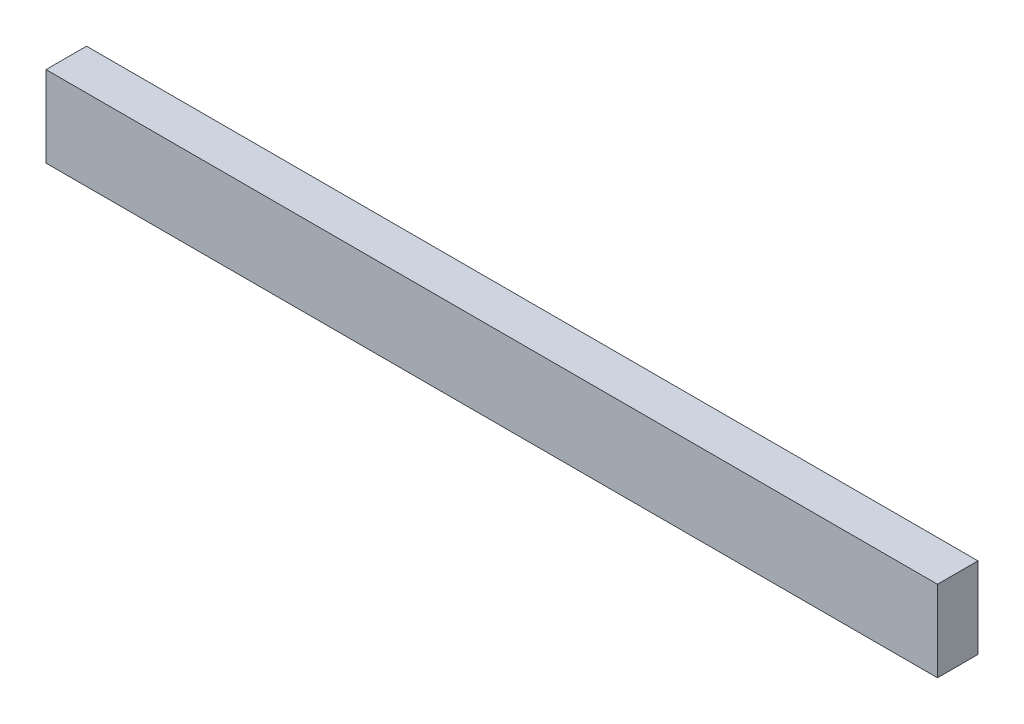
SolidWorks part; units mm, degrees
ref_plane "Front Plane" through (0, 0, 0) normal (0, 0, 1) x (1, 0, 0)
ref_plane "Top Plane" through (0, 0, 0) normal (0, 1, 0) x (1, 0, 0)
ref_plane "Right Plane" through (0, 0, 0) normal (1, 0, 0) x (0, 0, -1)
sketch "Sketch1" plane through (0, 0, 0) normal (0, 0, 1) x (1, 0, 0)
  line L1 (-34.925, -3.175) -> (34.925, -3.175)
  line L2 (-34.925, -3.175) -> (-34.925, 3.175)
  line L3 (-34.925, 3.175) -> (34.925, 3.175)
  line L4 (34.925, -3.175) -> (34.925, 3.175)
  line L5 (-34.925, -3.175) -> (34.925, 3.175) construction
  line L6 (-34.925, 3.175) -> (34.925, -3.175) construction
  point P0 (0, 0)
  dimension "D1" = 69.85
  dimension "D2" = 6.35
extrude "Boss-Extrude1" add sketch "Sketch1" along normal blind 3.175
